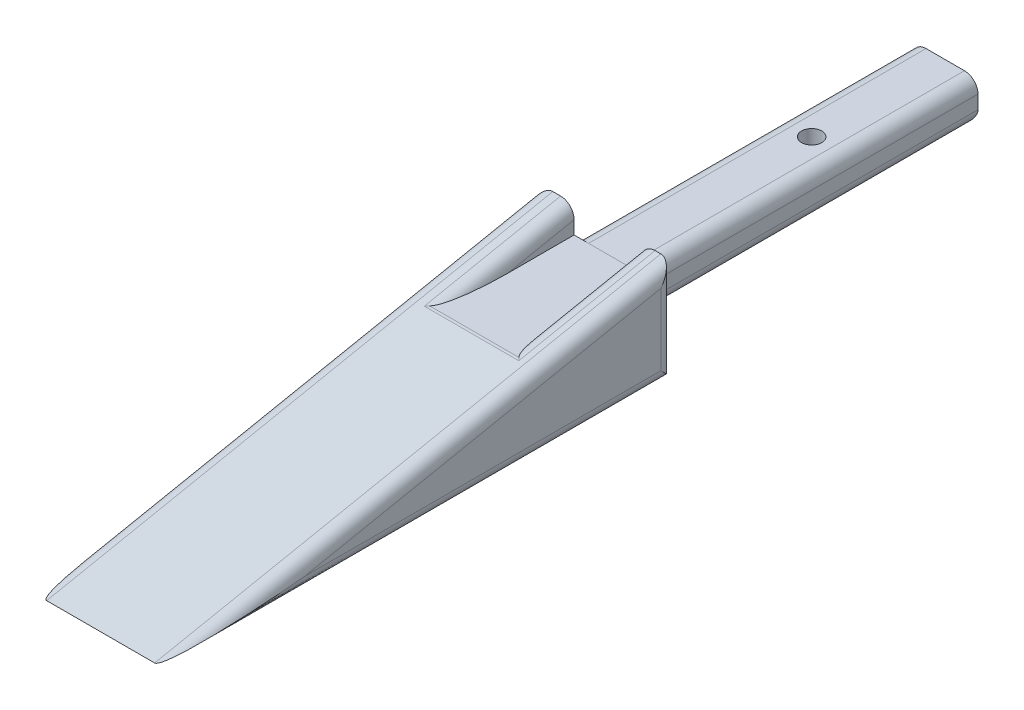
SolidWorks part; units mm, degrees
ref_plane "Front Plane" through (0, 0, 0) normal (0, 0, 1) x (1, 0, 0)
ref_plane "Top Plane" through (0, 0, 0) normal (0, 1, 0) x (1, 0, 0)
ref_plane "Right Plane" through (0, 0, 0) normal (1, 0, 0) x (0, 0, -1)
sketch "Sketch1" plane through (0, 0, 0) normal (0, 0, 1) x (1, 0, 0)
  line L1 (-4.85, -3) -> (4.85, -3)
  line L2 (-4.85, -3) -> (-4.85, 3)
  line L3 (-4.85, 3) -> (4.85, 3)
  line L4 (4.85, -3) -> (4.85, 3)
  line L5 (-4.85, -3) -> (4.85, 3) construction
  line L6 (-4.85, 3) -> (4.85, -3) construction
  point P0 (0, 0)
  dimension "D1" = 9.7
  dimension "D2" = 6
extrude "Boss-Extrude3" add sketch "Sketch1" along normal blind 50
sketch "Sketch3" plane through (4.85, 0, 0) normal (1, 0, 0) x (0, 0, -1)
  line L0 (-125, -8) -> (-50, -8)
  line L1 (-125, -8) -> (-50, 7)
  line L2 (-50, 7) -> (-50, -8)
  line L3 (-50, -3) -> (-50, 3) construction
  line L4 (-50, -3) -> (0, -3) construction
  dimension "D1" = 75
  dimension "D2" = 15
  dimension "D3" = 5
extrude "Boss-Extrude4" add sketch "Sketch3" against normal blind 20 from offset 5
fillet "Fillet1" radius 2 5 edges at (0, -3, 0) (-4.85, -3, 25) (-4.85, 3, 25) (4.85, -3, 25) (4.85, 3, 25)
sketch "Sketch6" plane through (0, 0, 0) normal (0, 0, -1) x (-1, 0, 0)
  line L0 (10.15, 7) -> (-9.85, 7) construction
  line L1 (-5, 3) -> (5, 3)
  line L2 (-5, 3) -> (-5, 7)
  line L3 (-5, 7) -> (5, 7)
  line L4 (5, 3) -> (5, 7)
  line L5 (-5, 3) -> (5, 7) construction
  line L6 (-5, 7) -> (5, 3) construction
  point P0 (0, 5)
  point P7 (0, 0)
  dimension "D1" = 10
  dimension "D2" = 4
extrude "Cut-Extrude1" cut sketch "Sketch6" against normal up to surface (70 mm away)
fillet "Fillet2" radius 2 9 edges at (-10.15, -8, 87.5) (-10.15, -0.5, 50) (-10.15, -0.5, 87.5) (-5, 5, 60) (5, 5, 60) (9.85, -8, 87.5) (9.85, -0.5, 50) (9.85, -0.5, 87.5) (0, 3, 70)
sketch "Sketch7" plane through (0, 3, 0) normal (0, 1, 0) x (1, 0, 0)
  line L0 (0, 0) -> (0, -50) construction
  line L1 (2.85, 0) -> (-2.85, 0) construction
  line L2 (5, -50) -> (-5, -50) construction
  circle A0 centre (0, -19.8) radius 1.5
  point P9 (-3.4858, -19.4908)
  dimension "D1" = 3
  dimension "D2" = 19.8
extrude "Cut-Extrude2" cut sketch "Sketch7" against normal blind 7
